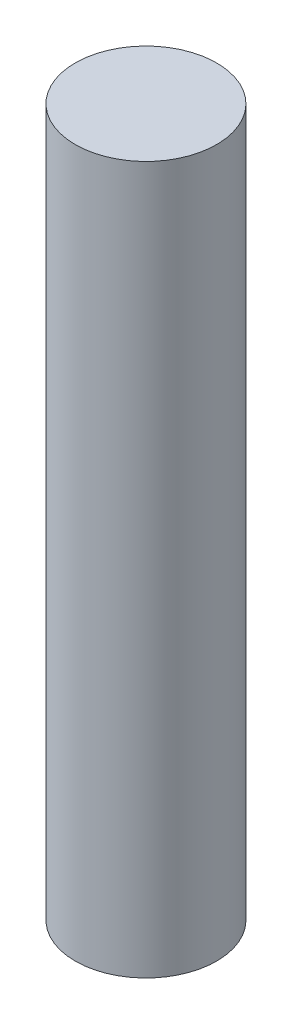
SolidWorks part; units mm, degrees
ref_plane "前视基准面" through (0, 0, 0) normal (0, 0, 1) x (1, 0, 0)
ref_plane "上视基准面" through (0, 0, 0) normal (0, 1, 0) x (1, 0, 0)
ref_plane "右视基准面" through (0, 0, 0) normal (1, 0, 0) x (0, 0, -1)
other "Configuration Table"
sketch "草图1" plane through (0, 0, 0) normal (0, 1, 0) x (1, 0, 0)
  circle A0 centre (0, 0) radius 1
  point P3 (0, 0)
  dimension "D1" = 2
extrude "凸台-拉伸1" add sketch "草图1" along normal blind 10
